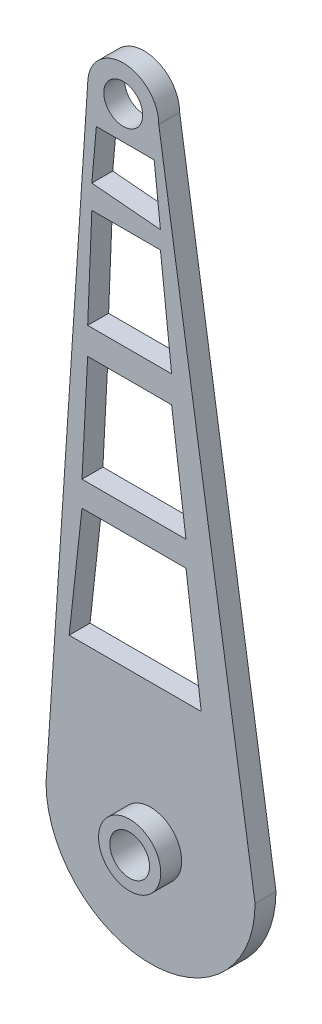
SolidWorks part; units mm, degrees
material "AISI 316 Stainless Steel Sheet (SS)"
ref_plane "Front Plane" through (0, 0, 0) normal (0, 0, 1) x (1, 0, 0)
ref_plane "Top Plane" through (0, 0, 0) normal (0, 1, 0) x (1, 0, 0)
ref_plane "Right Plane" through (0, 0, 0) normal (1, 0, 0) x (0, 0, -1)
sketch "Опорний" plane through (0, 0, 0) normal (0, 0, 1) x (1, 0, 0)
  line L0 (0, 0) -> (-6.5378, 149.8575) construction
  line L1 (-15.0378, 149.8575) -> (-25, 0)
  line L2 (1.9622, 149.8575) -> (25, 0)
  line L3 (-12.9625, 141.9699) -> (-14.0444, 129.7083)
  line L4 (-14.0444, 129.7083) -> (2.3676, 128.2602)
  line L5 (2.3676, 128.2602) -> (0.8619, 141.9699)
  line L6 (0.8619, 141.9699) -> (-12.9625, 141.9699)
  line L7 (-14.0444, 124.0583) -> (2.3676, 124.0583)
  line L8 (2.3676, 124.0583) -> (5.0392, 99.7326)
  line L9 (5.0392, 99.7326) -> (-15.0378, 99.7326)
  line L10 (-15.0378, 99.7326) -> (-14.0444, 124.0583)
  line L11 (-15.0378, 93.311) -> (5.0392, 93.311)
  line L12 (5.0392, 93.311) -> (8.4679, 67.1867)
  line L13 (8.4679, 67.1867) -> (-16.3991, 67.1867)
  line L14 (-16.3991, 67.1867) -> (-15.0378, 93.311)
  line L15 (-16.3991, 61.1795) -> (8.4679, 61.1795)
  line L16 (8.4679, 61.1795) -> (12.1236, 33.3268)
  line L17 (12.1236, 33.3268) -> (-19.4725, 33.3268)
  line L18 (-19.4725, 33.3268) -> (-16.3991, 61.1795)
  arc A0 (-25, 0) -> (25, 0) centre (0, 0) ccw
  arc A1 (1.9622, 149.8575) -> (-15.0378, 149.8575) centre (-6.5378, 149.8575) ccw
  circle A2 centre (-6.5378, 149.8575) radius 4.6578
  circle A3 centre (0, 0) radius 4.7666
  dimension "D1" = 50
  dimension "D3" = 17
  dimension "D4" = 150.1882
  dimension "D5" = 9.3156
  dimension "D6" = 9.5333
  dimension "D2" = 150
sketch "Sketch2" plane through (0, 0, 0) normal (0, 0, 1) x (1, 0, 0)
  line L0 (-19.4725, 33.3268) -> (-16.3991, 61.1795) construction
  line L1 (-16.3991, 61.1795) -> (8.4679, 61.1795) construction
  line L2 (8.4679, 61.1795) -> (12.1236, 33.3268) construction
  line L3 (12.1236, 33.3268) -> (-19.4725, 33.3268) construction
  line L4 (-16.3991, 67.1867) -> (-15.0378, 93.311) construction
  line L5 (-15.0378, 93.311) -> (5.0392, 93.311) construction
  line L6 (5.0392, 93.311) -> (8.4679, 67.1867) construction
  line L7 (8.4679, 67.1867) -> (-16.3991, 67.1867) construction
  line L8 (-15.0378, 99.7326) -> (-14.0444, 124.0583) construction
  line L9 (-14.0444, 124.0583) -> (2.3676, 124.0583) construction
  line L10 (2.3676, 124.0583) -> (5.0392, 99.7326) construction
  line L11 (5.0392, 99.7326) -> (-15.0378, 99.7326) construction
  line L12 (-12.9625, 141.9699) -> (-14.0444, 129.7083) construction
  line L13 (-14.0444, 129.7083) -> (2.3676, 128.2602) construction
  line L14 (2.3676, 128.2602) -> (0.8619, 141.9699) construction
  line L15 (0.8619, 141.9699) -> (-12.9625, 141.9699) construction
  line L16 (-15.0378, 149.8575) -> (-25, 0) construction
  line L17 (1.9622, 149.8575) -> (25, 0) construction
  line L18 (-19.4725, 33.3268) -> (-16.3991, 61.1795)
  line L19 (-16.3991, 61.1795) -> (8.4679, 61.1795)
  line L20 (8.4679, 61.1795) -> (12.1236, 33.3268)
  line L21 (12.1236, 33.3268) -> (-19.4725, 33.3268)
  line L22 (-16.3991, 67.1867) -> (-15.0378, 93.311)
  line L23 (-15.0378, 93.311) -> (5.0392, 93.311)
  line L24 (5.0392, 93.311) -> (8.4679, 67.1867)
  line L25 (8.4679, 67.1867) -> (-16.3991, 67.1867)
  line L26 (-15.0378, 99.7326) -> (-14.0444, 124.0583)
  line L27 (-14.0444, 124.0583) -> (2.3676, 124.0583)
  line L28 (2.3676, 124.0583) -> (5.0392, 99.7326)
  line L29 (5.0392, 99.7326) -> (-15.0378, 99.7326)
  line L30 (-12.9625, 141.9699) -> (-14.0444, 129.7083)
  line L31 (-14.0444, 129.7083) -> (2.3676, 128.2602)
  line L32 (2.3676, 128.2602) -> (0.8619, 141.9699)
  line L33 (0.8619, 141.9699) -> (-12.9625, 141.9699)
  line L34 (-15.0378, 149.8575) -> (-25, 0)
  line L35 (1.9622, 149.8575) -> (25, 0)
  circle A0 centre (0, 0) radius 4.7666 construction
  circle A1 centre (-6.5378, 149.8575) radius 4.6578 construction
  arc A2 (-25, 0) -> (25, 0) centre (0, 0) ccw construction
  arc A3 (1.9622, 149.8575) -> (-15.0378, 149.8575) centre (-6.5378, 149.8575) ccw construction
  circle A4 centre (0, 0) radius 4.7666
  circle A5 centre (-6.5378, 149.8575) radius 4.6578
  arc A6 (-25, 0) -> (25, 0) centre (0, 0) ccw
  arc A7 (1.9622, 149.8575) -> (-15.0378, 149.8575) centre (-6.5378, 149.8575) ccw
extrude "Boss-Extrude1" add sketch "Sketch2" along normal blind 5
sketch "Sketch3" plane through (0, 0, 5) normal (0, 0, 1) x (1, 0, 0)
  circle A0 centre (0, 0) radius 4.7666 construction
  circle A1 centre (0, 0) radius 4.7666
  circle A2 centre (0, 0) radius 7.4438
extrude "Boss-Extrude2" add sketch "Sketch3" along normal blind 5
